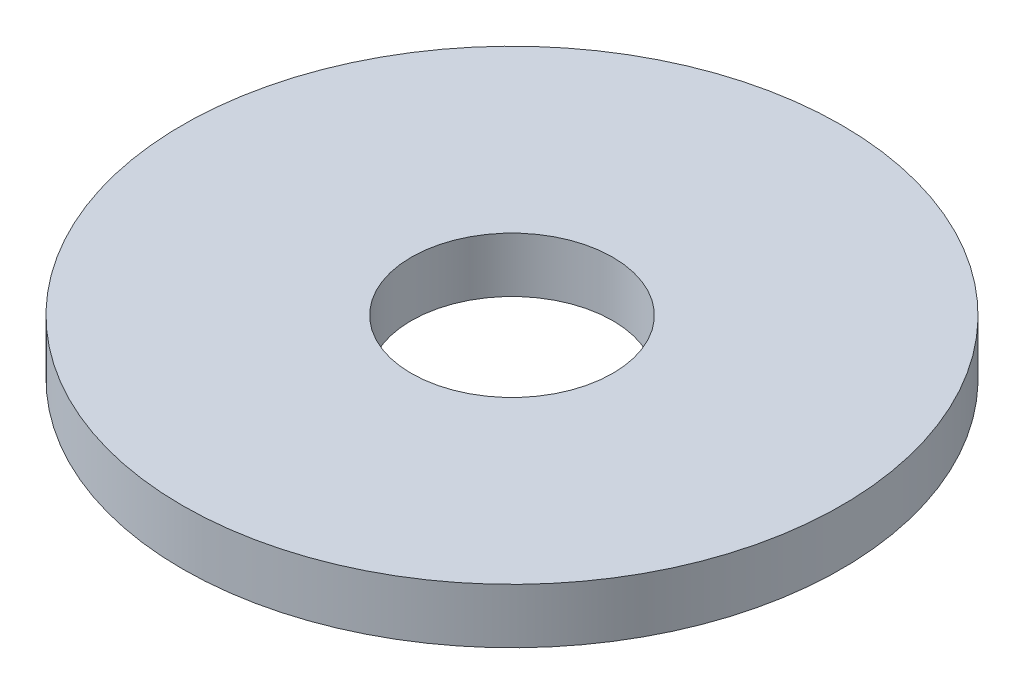
SolidWorks part; units mm, degrees
ref_plane "Plane1" through (0, 0, 0) normal (0, 0, 1) x (1, 0, 0)
ref_plane "Plane2" through (0, 0, 0) normal (0, 1, 0) x (1, 0, 0)
ref_plane "Plane3" through (0, 0, 0) normal (1, 0, 0) x (0, 0, -1)
sketch "Sketch1" plane through (0, 0, 0) normal (0, 1, 0) x (1, 0, 0)
  circle A0 centre (0, 0) radius 36
  dimension "OutsideDia" = 72
extrude "Base-Extrude" add sketch "Sketch1" against normal blind 6
sketch "Sketch2" plane through (0, 0, 0) normal (0, 1, 0) x (-1, 0, 0)
  circle A0 centre (0, 0) radius 11
  dimension "HoleDia" = 22
extrude "Type-R" cut sketch "Sketch2" against normal through all
sketch "Sketch3" plane through (0, 0, 0) normal (0, 1, 0) x (-1, 0, 0)
  line L1 (11, 11) -> (-11, 11)
  line L2 (11, 11) -> (11, -11)
  line L3 (11, -11) -> (-11, -11)
  line L4 (-11, 11) -> (-11, -11)
  dimension "SquareSize" = 22
  dimension "D1" = 22
  dimension "D2" = 11
  dimension "D3" = 11
extrude "Type-V" [suppressed] cut sketch "Sketch3" against normal through all
equation "\"D1@Sketch3\" = \"SquareSize@Sketch3\""
equation "\"D2@Sketch3\" = \"SquareSize@Sketch3\" / 2"
equation "\"D3@Sketch3\" = \"D1@Sketch3\" / 2"
